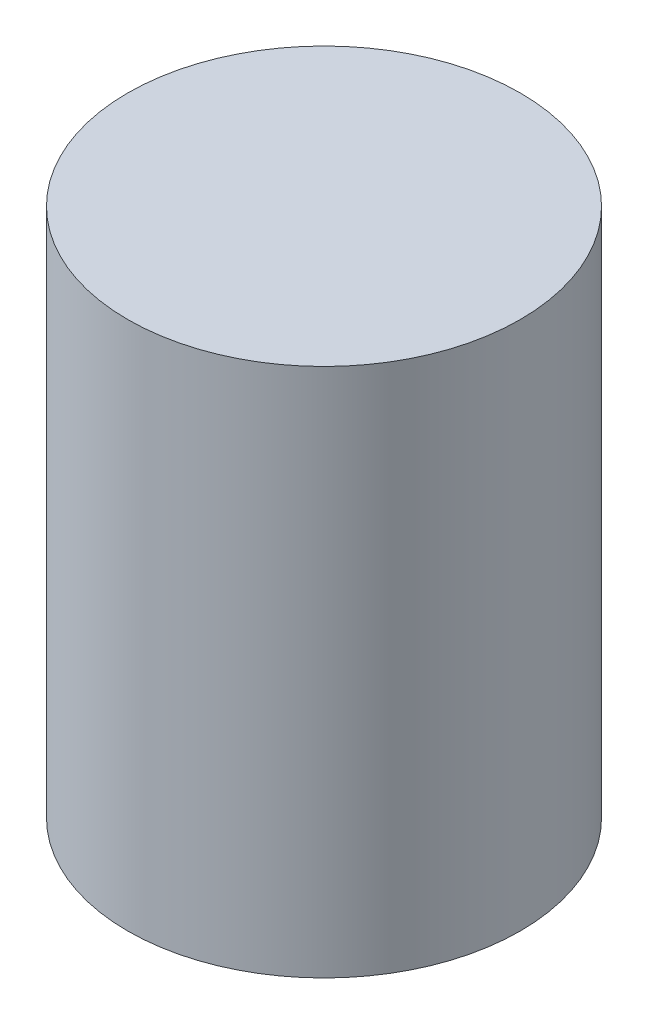
SolidWorks part; units mm, degrees
ref_plane "Front Plane" through (0, 0, 0) normal (0, 0, 1) x (1, 0, 0)
ref_plane "Top Plane" through (0, 0, 0) normal (0, 1, 0) x (1, 0, 0)
ref_plane "Right Plane" through (0, 0, 0) normal (1, 0, 0) x (0, 0, -1)
sketch "CurveSketch" plane through (0, 0, 0) normal (0, 1, 0) x (1, 0, 0)
  circle A0 centre (-6.193, 8.723) radius 11.231
  dimension "D1" = 22.462
extrude "CurveBoss" add sketch "CurveSketch" against normal blind 21.389 and the other way blind 8.917
